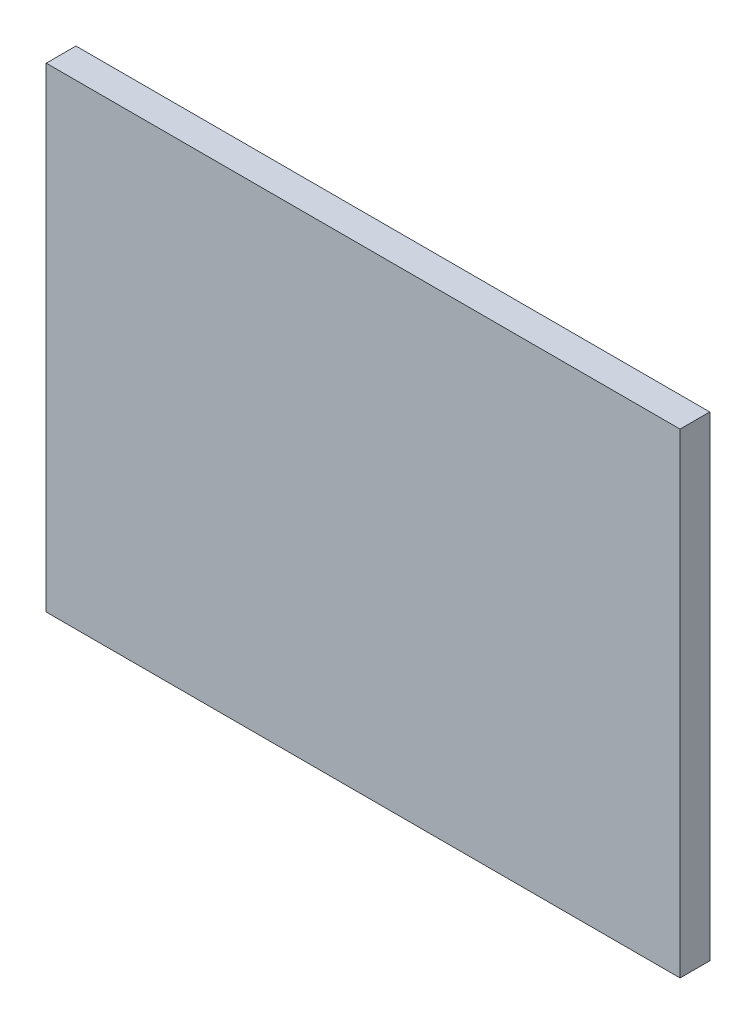
SolidWorks part; units mm, degrees
ref_plane "Front" through (0, 0, 0) normal (0, 0, 1) x (1, 0, 0)
ref_plane "Top" through (0, 0, 0) normal (0, 1, 0) x (1, 0, 0)
ref_plane "Right" through (0, 0, 0) normal (1, 0, 0) x (0, 0, -1)
other "Configuration Table"
sketch "Sketch1" plane through (0, 0, 0) normal (0, 0, 1) x (1, 0, 0)
  line L1 (-100.4004, -228.2088) -> (305.9996, -228.2088)
  line L2 (-100.4004, -228.2088) -> (-100.4004, 76.5912)
  line L3 (-100.4004, 76.5912) -> (305.9996, 76.5912)
  line L4 (305.9996, -228.2088) -> (305.9996, 76.5912)
  dimension "D1" = 406.4
  dimension "D2" = 304.8
extrude "Base-Extrude" add sketch "Sketch1" along normal blind 19.05
